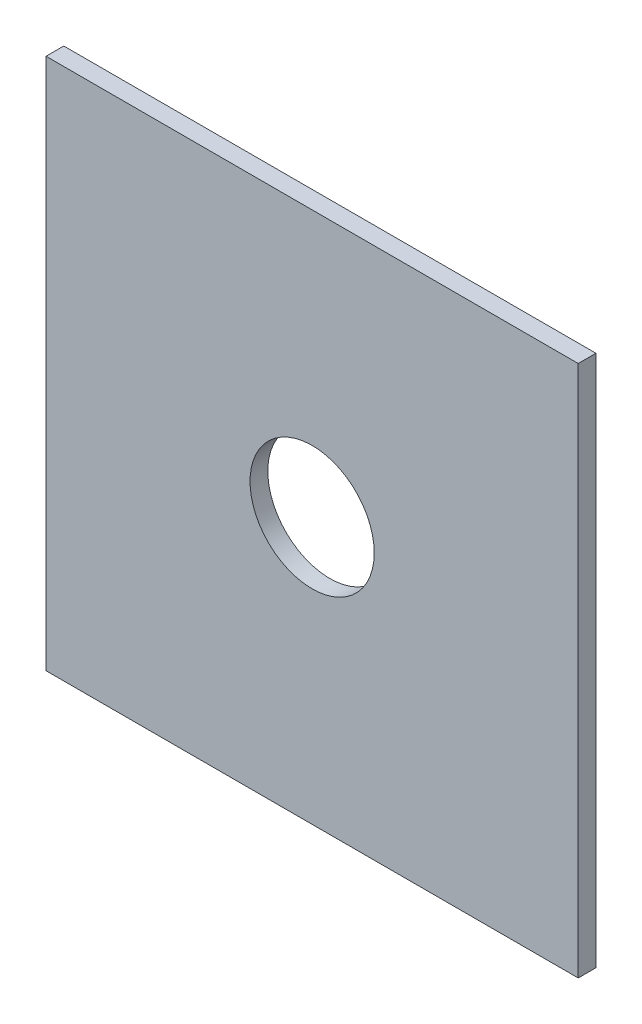
SolidWorks part; units mm, degrees
ref_plane "Alzado" through (0, 0, 0) normal (0, 0, 1) x (1, 0, 0)
ref_plane "Planta" through (0, 0, 0) normal (0, 1, 0) x (1, 0, 0)
ref_plane "Vista lateral" through (0, 0, 0) normal (1, 0, 0) x (0, 0, -1)
sketch "Croquis1" plane through (0, 0, 0) normal (0, 0, 1) x (1, 0, 0)
  line L1 (-7.5, 7.5) -> (7.5, 7.5)
  line L2 (-7.5, 7.5) -> (-7.5, -7.5)
  line L3 (-7.5, -7.5) -> (7.5, -7.5)
  line L4 (7.5, 7.5) -> (7.5, -7.5)
  line L5 (-7.5, 7.5) -> (7.5, -7.5) construction
  line L6 (-7.5, -7.5) -> (7.5, 7.5) construction
  point P0 (0, 0)
  dimension "D1" = 15
  dimension "D2" = 15
extrude "Saliente-Extruir1" add sketch "Croquis1" along normal blind 0.5
sketch "Croquis2" plane through (0, 0, 0.5) normal (0, 0, 1) x (1, 0, 0)
  circle A0 centre (0, 0) radius 1.75
  dimension "D1" = 3.5
extrude "Cortar-Extruir1" cut sketch "Croquis2" against normal blind 0.5
